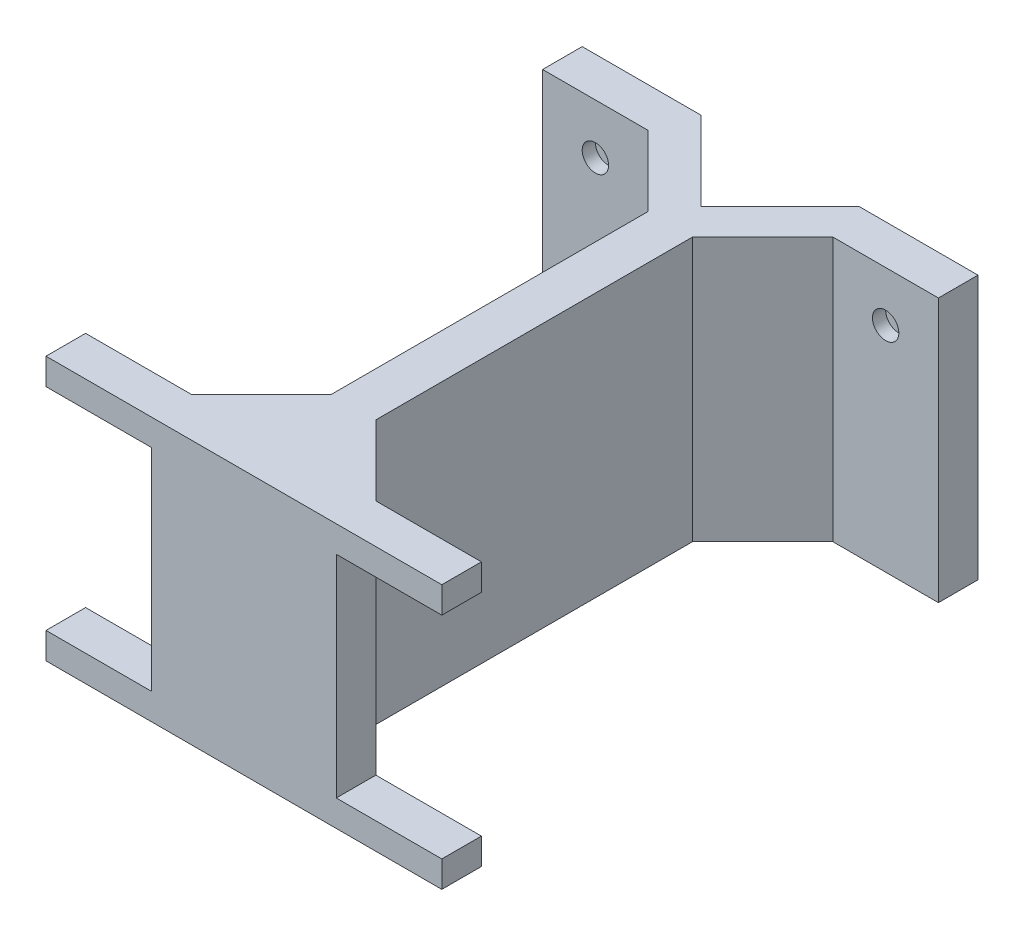
SolidWorks part; units mm, degrees
ref_plane "Front Plane" through (0, 0, 0) normal (0, 0, 1) x (1, 0, 0)
ref_plane "Top Plane" through (0, 0, 0) normal (0, 1, 0) x (1, 0, 0)
ref_plane "Right Plane" through (0, 0, 0) normal (1, 0, 0) x (0, 0, -1)
sketch "Sketch2" plane through (0, 0, 0) normal (0, 0, 1) x (1, 0, 0)
  line L1 (-40.8077, 18.1865) -> (34.1923, 18.1865)
  line L2 (-40.8077, 18.1865) -> (-40.8077, -31.8135)
  line L3 (-40.8077, -31.8135) -> (34.1923, -31.8135)
  line L4 (34.1923, 18.1865) -> (34.1923, -31.8135)
  dimension "D1" = 75
  dimension "D2" = 50
extrude "Boss-Extrude1" add sketch "Sketch2" along normal blind 101.6
sketch "Sketch3" plane through (0, 18.1865, 0) normal (0, 1, 0) x (1, 0, 0)
  line L0 (-40.8077, -7.5) -> (-20.8077, -7.5)
  line L1 (-40.8077, -101.6) -> (-40.8077, 0) construction
  line L2 (-20.8077, -7.5) -> (-7.5077, -20.8)
  line L3 (-7.5077, -20.8) -> (-7.5077, -80.8)
  line L4 (-7.5077, -80.8) -> (-20.8077, -94.1)
  line L5 (-20.8077, -94.1) -> (-40.8077, -94.1)
  line L6 (-40.8077, -94.1) -> (-40.8077, -7.5)
  line L7 (34.1923, -101.6) -> (-40.8077, -101.6) construction
  line L8 (34.1923, 0) -> (-40.8077, 0) construction
  dimension "D1" = 7.5
  dimension "D2" = 7.5
  dimension "D3" = 20
  dimension "D4" = 20
  dimension "D5" = 135
  dimension "D6" = 60
extrude "Cut-Extrude1" cut sketch "Sketch3" against normal blind 101.6
sketch "Sketch4" plane through (0, 18.1865, 0) normal (0, 1, 0) x (1, 0, 0)
  line L0 (34.1923, -94.1) -> (14.1923, -94.1)
  line L1 (34.1923, -101.6) -> (34.1923, 0) construction
  line L2 (14.1923, -94.1) -> (0.8923, -80.8)
  line L3 (0.8923, -80.8) -> (0.8923, -20.8)
  line L4 (0.8923, -20.8) -> (14.1923, -7.5)
  line L5 (14.1923, -7.5) -> (34.1923, -7.5)
  line L6 (34.1923, -7.5) -> (34.1923, -94.1)
  line L7 (34.1923, -101.6) -> (-40.8077, -101.6) construction
  line L8 (34.1923, 0) -> (-40.8077, 0) construction
  dimension "D1" = 7.5
  dimension "D2" = 7.5
  dimension "D3" = 20
  dimension "D4" = 20
  dimension "D5" = 135
  dimension "D6" = 135
  dimension "D7" = 60
extrude "Cut-Extrude2" cut sketch "Sketch4" against normal blind 101.6
sketch "Sketch5" plane through (0, 0, 101.6) normal (0, 0, 1) x (1, 0, 0)
  line L0 (34.1923, -31.8135) -> (34.1923, 18.1865) construction
  line L1 (34.1923, -26.8135) -> (14.1923, -26.8135)
  line L2 (34.1923, -26.8135) -> (34.1923, 13.1865)
  line L3 (34.1923, 13.1865) -> (14.1923, 13.1865)
  line L4 (14.1923, -26.8135) -> (14.1923, 13.1865)
  line L5 (-40.8077, -31.8135) -> (34.1923, -31.8135) construction
  dimension "D1" = 5
  dimension "D2" = 40
  dimension "D3" = 20
extrude "Cut-Extrude3" cut sketch "Sketch5" against normal blind 10
sketch "Sketch6" plane through (0, 0, 101.6) normal (0, 0, 1) x (1, 0, 0)
  line L0 (-40.8077, 18.1865) -> (-40.8077, -31.8135) construction
  line L1 (-40.8077, 13.1865) -> (-20.8077, 13.1865)
  line L2 (-40.8077, 13.1865) -> (-40.8077, -26.8135)
  line L3 (-40.8077, -26.8135) -> (-20.8077, -26.8135)
  line L4 (-20.8077, 13.1865) -> (-20.8077, -26.8135)
  line L5 (34.1923, 18.1865) -> (-40.8077, 18.1865) construction
  dimension "D1" = 20
  dimension "D2" = 40
  dimension "D3" = 5
extrude "Cut-Extrude4" cut sketch "Sketch6" against normal blind 10
sketch "Sketch7" plane through (0, 0, 7.5) normal (0, 0, 1) x (1, 0, 0)
  line L0 (34.1923, 18.1865) -> (14.1923, 18.1865) construction
  line L1 (14.1923, -31.8135) -> (14.1923, 18.1865) construction
  circle A0 centre (24.1923, 8.6865) radius 2.5
  dimension "D1" = 9.5
  dimension "D2" = 10
extrude "Cut-Extrude5" cut sketch "Sketch7" against normal blind 2.5
sketch "Sketch8" plane through (0, 0, 7.5) normal (0, 0, 1) x (1, 0, 0)
  line L0 (-20.8077, 18.1865) -> (-40.8077, 18.1865) construction
  line L1 (-40.8077, -31.8135) -> (-40.8077, 18.1865) construction
  circle A0 centre (-30.8077, 8.6865) radius 2.5
  point P6 (-31.3721, 8.6974)
  dimension "D1" = 9.5
  dimension "D2" = 10
extrude "Cut-Extrude6" cut sketch "Sketch8" against normal blind 2.5 contours A0
sketch "Sketch9" plane through (0, 18.1865, 0) normal (0, 1, 0) x (1, 0, 0)
  line L0 (-18.2482, 0) -> (-3.3077, -14.9405)
  line L1 (34.1923, 0) -> (-40.8077, 0) construction
  line L2 (-3.3077, -14.9405) -> (11.6328, 0)
  line L3 (11.6328, 0) -> (-18.2482, 0)
  line L4 (-7.5077, -20.8) -> (-20.8077, -7.5) construction
  line L5 (14.1923, -7.5) -> (0.8923, -20.8) construction
  line L6 (-40.8077, -7.5) -> (-40.8077, 0) construction
  point P13 (-40.8077, -1.9607)
  dimension "D1" = 37.5
extrude "Cut-Extrude7" cut sketch "Sketch9" against normal through all
